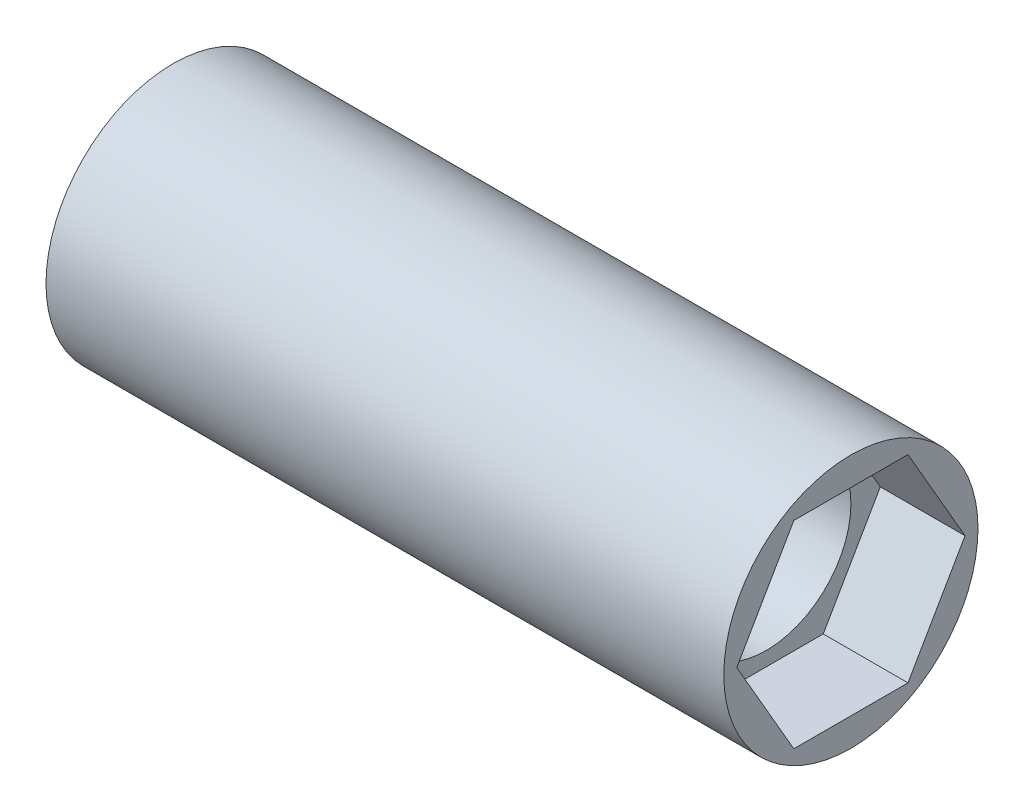
SolidWorks part; units mm, degrees
ref_plane "Płaszczyzna przednia" through (0, 0, 0) normal (0, 0, 1) x (1, 0, 0)
ref_plane "Płaszczyzna górna" through (0, 0, 0) normal (0, 1, 0) x (1, 0, 0)
ref_plane "Płaszczyzna prawa" through (0, 0, 0) normal (1, 0, 0) x (0, 0, -1)
sketch "Szkic1" plane through (0, 0, 0) normal (1, 0, 0) x (0, 0, -1)
  circle A0 centre (0, 0) radius 4.5
  circle A1 centre (0, 0) radius 3
  dimension "D1" = 9
  dimension "D2" = 6
extrude "Dodanie-wyciągnięcie1" add sketch "Szkic1" along normal blind 24
sketch "Szkic2" plane through (24, 0, 0) normal (1, 0, 0) x (0, 0, -1)
  line L1 (4.0415, 0) -> (2.0207, 3.5)
  line L2 (2.0207, 3.5) -> (-2.0207, 3.5)
  line L3 (-2.0207, 3.5) -> (-4.0415, 0)
  line L4 (-4.0415, 0) -> (-2.0207, -3.5)
  line L5 (-2.0207, -3.5) -> (2.0207, -3.5)
  line L6 (2.0207, -3.5) -> (4.0415, 0)
  circle A0 centre (0, 0) radius 3.5 construction
  dimension "D1" = 7
extrude "Wytnij-wyciągnięcie1" cut sketch "Szkic2" against normal blind 3
